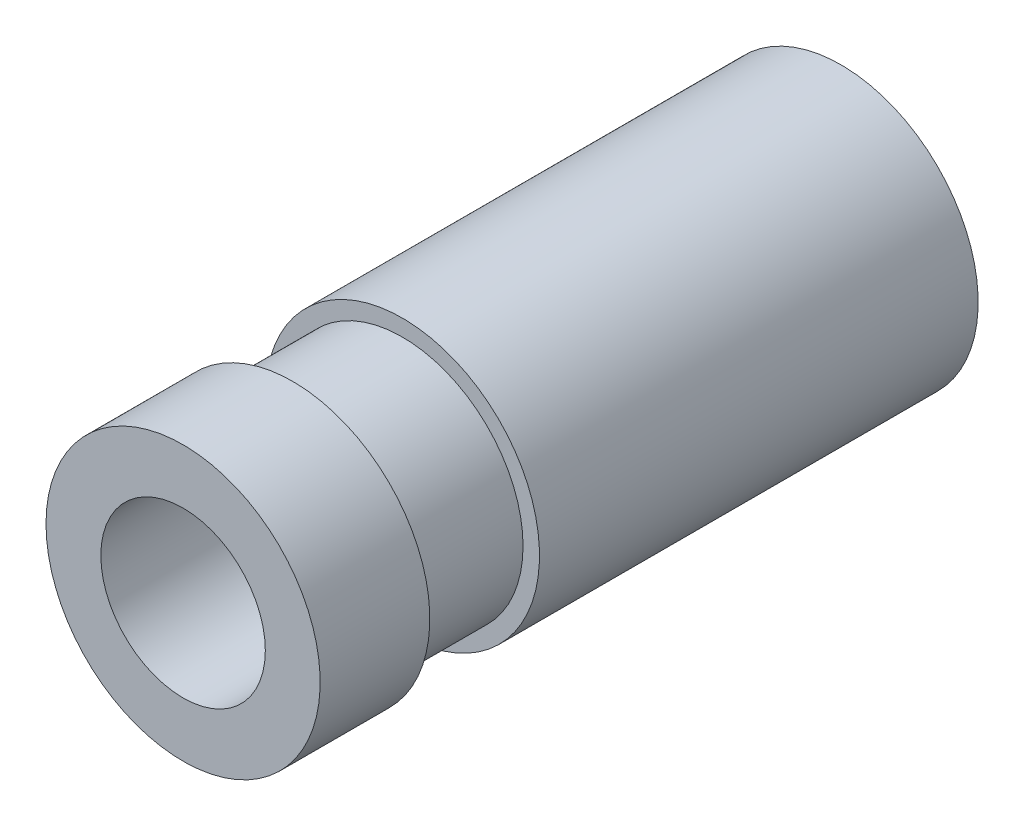
SolidWorks part; units mm, degrees
ref_plane "Front Plane" through (0, 0, 0) normal (0, 0, 1) x (1, 0, 0)
ref_plane "Top Plane" through (0, 0, 0) normal (0, 1, 0) x (1, 0, 0)
ref_plane "Right Plane" through (0, 0, 0) normal (1, 0, 0) x (0, 0, -1)
sketch "Sketch1" plane through (0, 0, 0) normal (0, 0, 1) x (1, 0, 0)
  circle A0 centre (0, 0) radius 1.5875
  circle A1 centre (0, 0) radius 0.9525
  dimension "D1" = 1.905
  dimension "D2" = 3.175
extrude "Boss-Extrude1" add sketch "Sketch1" along normal blind 7.62
ref_plane "Plane1" through (0, 0, 6.35) normal (0, 0, 1) x (1, 0, 0)
sketch "Sketch2" plane through (0, 0, 6.35) normal (0, 0, 1) x (1, 0, 0)
  circle A0 centre (0, 0) radius 1.397
  circle A1 centre (0, 0) radius 1.5875
  point P5 (0, 0)
  dimension "D1" = 2.794
  dimension "D2" = 3.175
extrude "Cut-Extrude1" cut sketch "Sketch2" against normal blind 1.27
